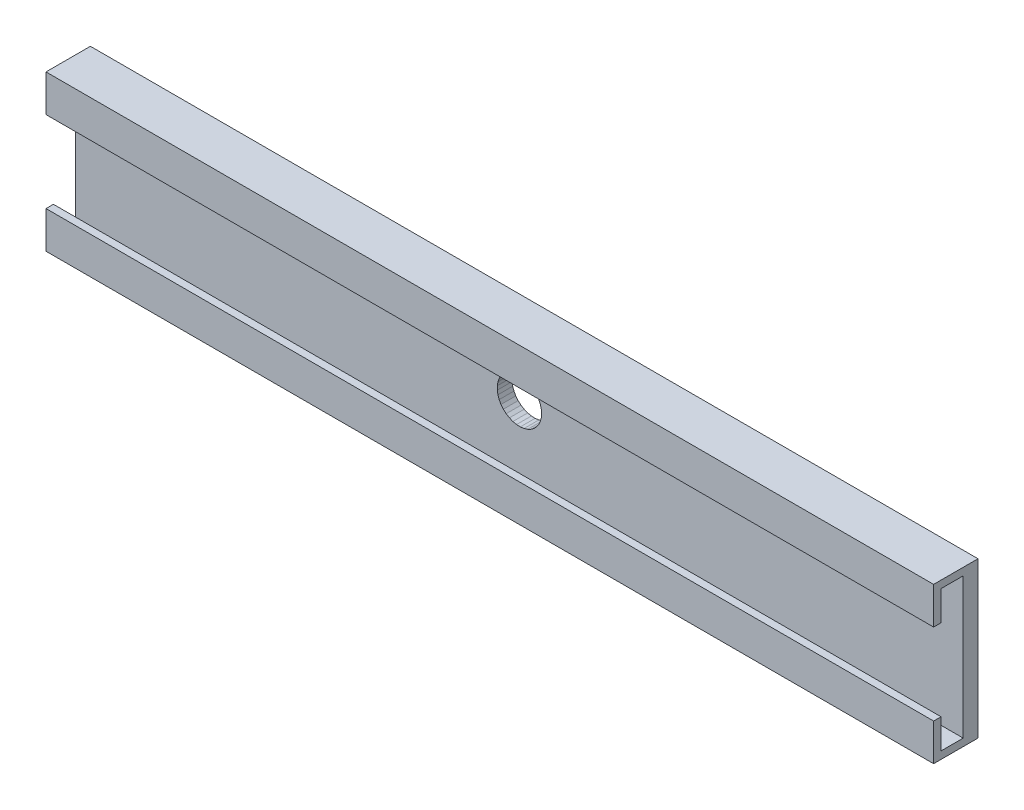
SolidWorks part; units mm, degrees
ref_plane "Front Plane" through (0, 0, 0) normal (0, 0, 1) x (1, 0, 0)
ref_plane "Top Plane" through (0, 0, 0) normal (0, 1, 0) x (1, 0, 0)
ref_plane "Right Plane" through (0, 0, 0) normal (1, 0, 0) x (0, 0, -1)
ref_plane "Plane1" through (0, 0, 0) normal (0, 0, -1) x (-1, 0, 0)
sketch "Sketch1" plane through (0, 0, 0) normal (0, 0, -1) x (-1, 0, 0)
  line L0 (-60, 10.5) -> (-60, 0)
  line L1 (-60, 0) -> (0, 0)
  line L2 (0, 0) -> (0, 10.5)
  line L3 (0, 10.5) -> (-60, 10.5)
extrude "Boss-Extrude1" add sketch "Sketch1" against normal blind 3
sketch "Sketch2" plane through (0, 0, 0) normal (-1, 0, 0) x (0, 0, 1)
  line L0 (3, 2.5) -> (3, 8)
  line L1 (3, 8) -> (2.5, 8)
  line L2 (2.5, 8) -> (2.5, 10)
  line L3 (2.5, 10) -> (1, 10)
  line L4 (1, 10) -> (1, 0.5)
  line L5 (1, 0.5) -> (2.5, 0.5)
  line L6 (2.5, 0.5) -> (2.5, 2.5)
  line L7 (2.5, 2.5) -> (3, 2.5)
extrude "Cut-Extrude1" cut sketch "Sketch2" against normal through all
sketch "Sketch3" plane through (0, 0, 1) normal (0, 0, 1) x (1, 0, 0)
  line L0 (30.5593, 6.6418) -> (30.316, 6.7163)
  line L1 (30.316, 6.7163) -> (30.0637, 6.7486)
  line L2 (30.0637, 6.7486) -> (29.8095, 6.7379)
  line L3 (29.8095, 6.7379) -> (29.5608, 6.6843)
  line L4 (29.5608, 6.6843) -> (29.3247, 6.5894)
  line L5 (29.3247, 6.5894) -> (29.108, 6.456)
  line L6 (29.108, 6.456) -> (28.9171, 6.2879)
  line L7 (28.9171, 6.2879) -> (28.7572, 6.09)
  line L8 (28.7572, 6.09) -> (28.6332, 5.8679)
  line L9 (28.6332, 5.8679) -> (28.5484, 5.628)
  line L10 (28.5484, 5.628) -> (28.5054, 5.3772)
  line L11 (28.5054, 5.3772) -> (28.5054, 5.1228)
  line L12 (28.5054, 5.1228) -> (28.5484, 4.872)
  line L13 (28.5484, 4.872) -> (28.6332, 4.6321)
  line L14 (28.6332, 4.6321) -> (28.7572, 4.41)
  line L15 (28.7572, 4.41) -> (28.9171, 4.2121)
  line L16 (28.9171, 4.2121) -> (29.108, 4.044)
  line L17 (29.108, 4.044) -> (29.3247, 3.9106)
  line L18 (29.3247, 3.9106) -> (29.5608, 3.8157)
  line L19 (29.5608, 3.8157) -> (29.8095, 3.7621)
  line L20 (29.8095, 3.7621) -> (30.0637, 3.7514)
  line L21 (30.0637, 3.7514) -> (30.316, 3.7837)
  line L22 (30.316, 3.7837) -> (30.5593, 3.8582)
  line L23 (30.5593, 3.8582) -> (30.7865, 3.9727)
  line L24 (30.7865, 3.9727) -> (30.991, 4.124)
  line L25 (30.991, 4.124) -> (31.1671, 4.3077)
  line L26 (31.1671, 4.3077) -> (31.3095, 4.5185)
  line L27 (31.3095, 4.5185) -> (31.4143, 4.7503)
  line L28 (31.4143, 4.7503) -> (31.4784, 4.9965)
  line L29 (31.4784, 4.9965) -> (31.5, 5.25)
  line L30 (31.5, 5.25) -> (31.4784, 5.5035)
  line L31 (31.4784, 5.5035) -> (31.4143, 5.7497)
  line L32 (31.4143, 5.7497) -> (31.3095, 5.9815)
  line L33 (31.3095, 5.9815) -> (31.1671, 6.1923)
  line L34 (31.1671, 6.1923) -> (30.991, 6.376)
  line L35 (30.991, 6.376) -> (30.7865, 6.5273)
  line L36 (30.7865, 6.5273) -> (30.5593, 6.6418)
extrude "Cut-Extrude2" cut sketch "Sketch3" against normal through all
